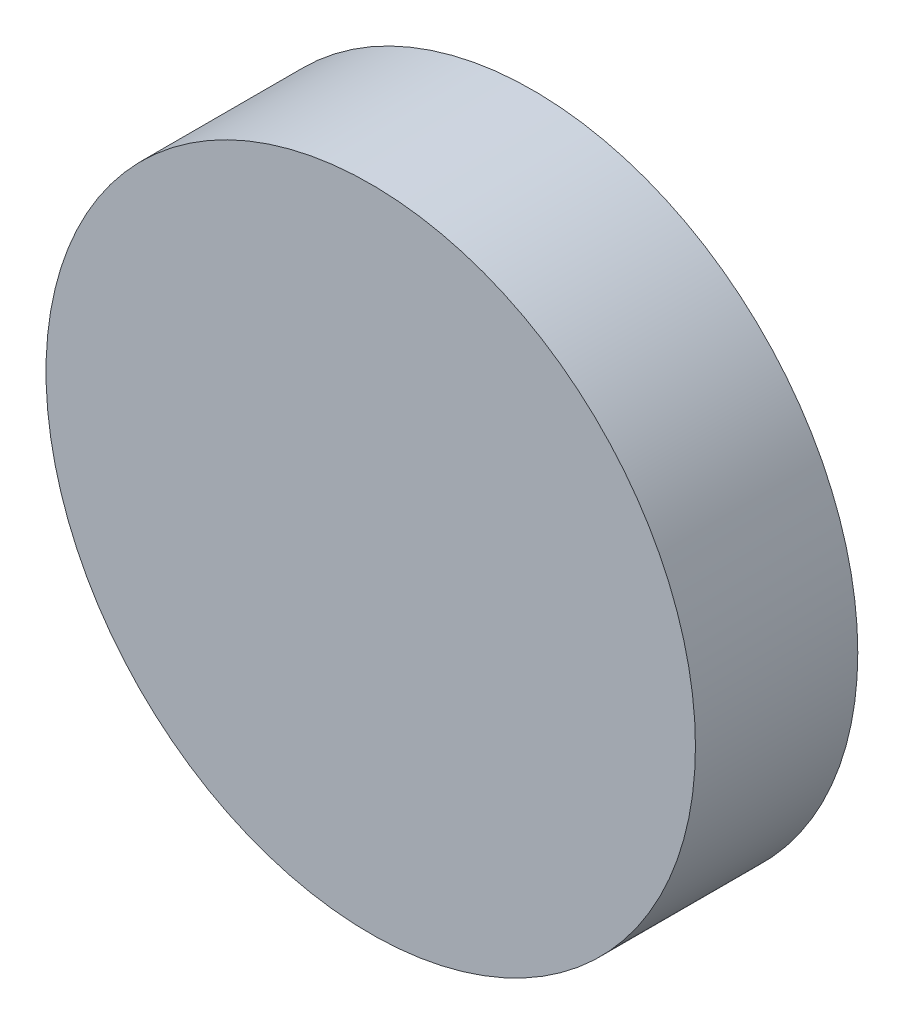
SolidWorks part; units mm, degrees
ref_plane "Front Plane" through (0, 0, 0) normal (0, 0, 1) x (1, 0, 0)
ref_plane "Top Plane" through (0, 0, 0) normal (0, 1, 0) x (1, 0, 0)
ref_plane "Right Plane" through (0, 0, 0) normal (1, 0, 0) x (0, 0, -1)
sketch "Sketch1" plane through (0, 0, 0) normal (0, 0, 1) x (1, 0, 0)
  circle A0 centre (0, 0) radius 2
  dimension "D1" = 4
extrude "Boss-Extrude1" add sketch "Sketch1" along normal blind 1
